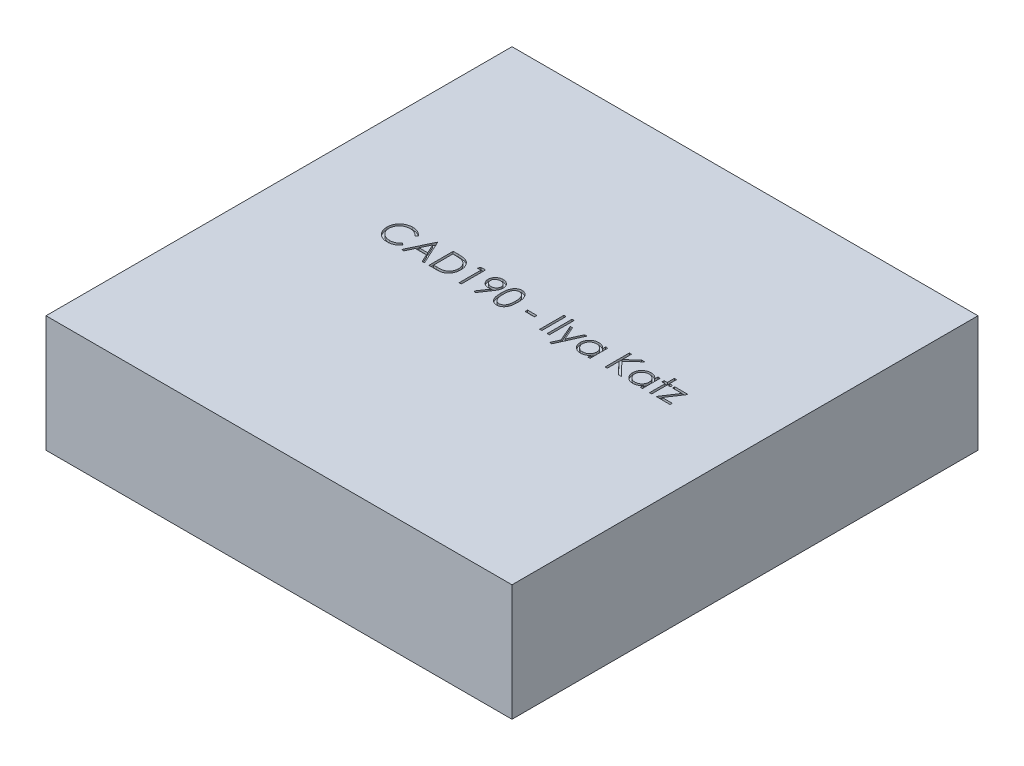
SolidWorks part; units mm, degrees
ref_plane "Front Plane" through (0, 0, 0) normal (0, 0, 1) x (1, 0, 0)
ref_plane "Top Plane" through (0, 0, 0) normal (0, 1, 0) x (1, 0, 0)
ref_plane "Right Plane" through (0, 0, 0) normal (1, 0, 0) x (0, 0, -1)
sketch "Sketch1" plane through (0, 0, 0) normal (0, 1, 0) x (1, 0, 0)
  line L1 (0, 0) -> (50.8, 0)
  line L2 (0, 0) -> (0, -50.8)
  line L3 (0, -50.8) -> (50.8, -50.8)
  line L4 (50.8, 0) -> (50.8, -50.8)
  dimension "D1" = 50.8
  dimension "D2" = 50.8
extrude "Boss-Extrude1" add sketch "Sketch1" along normal blind 12.7
sketch "Sketch2" plane through (0, 12.7, 0) normal (0, 1, 0) x (1, 0, 0)
  text T0 "CAD190 - Ilya Katz" font "Century Gothic" height in points 10
extrude "Cut-Extrude1" cut sketch "Sketch2" against normal blind 0.254
